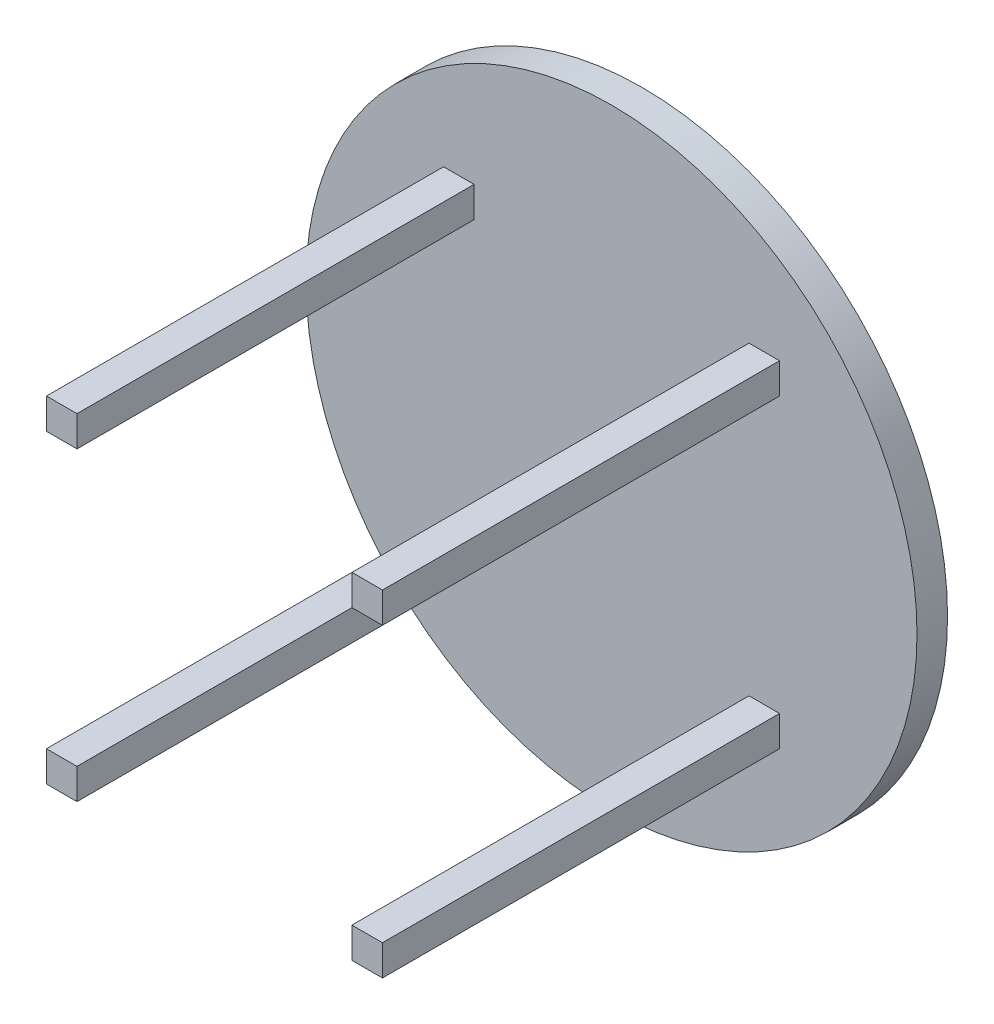
SolidWorks part; units mm, degrees
ref_plane "前视基准面" through (0, 0, 0) normal (0, 0, 1) x (1, 0, 0)
ref_plane "上视基准面" through (0, 0, 0) normal (0, 1, 0) x (1, 0, 0)
ref_plane "右视基准面" through (0, 0, 0) normal (1, 0, 0) x (0, 0, -1)
other "Configuration Table"
sketch "草图1" plane through (0, 0, 0) normal (0, 0, 1) x (1, 0, 0)
  circle A0 centre (0, 0) radius 500
extrude "凸台-拉伸1" add sketch "草图1" along normal blind 50
sketch "草图2" plane through (0, 0, 0) normal (0, 0, 1) x (1, 0, 0)
  line L1 (225, 225) -> (275, 225)
  line L2 (225, 225) -> (225, 275)
  line L3 (225, 275) -> (275, 275)
  line L4 (275, 225) -> (275, 275)
  line L5 (225, 225) -> (275, 275) construction
  line L6 (225, 275) -> (275, 225) construction
  point P0 (250, 250)
extrude "凸台-拉伸2" add sketch "草图2" along normal blind 700
sketch "草图3" plane through (0, 0, 0) normal (0, 0, 1) x (1, 0, 0)
  line L1 (-275, 225) -> (-225, 225)
  line L2 (-275, 225) -> (-275, 275)
  line L3 (-275, 275) -> (-225, 275)
  line L4 (-225, 225) -> (-225, 275)
  line L5 (-275, 225) -> (-225, 275) construction
  line L6 (-275, 275) -> (-225, 225) construction
  point P0 (-250, 250)
extrude "凸台-拉伸3" add sketch "草图3" along normal blind 700
sketch "草图4" plane through (0, 0, 0) normal (0, 0, 1) x (1, 0, 0)
  line L1 (225, -275) -> (275, -275)
  line L2 (225, -275) -> (225, -225)
  line L3 (225, -225) -> (275, -225)
  line L4 (275, -275) -> (275, -225)
  line L5 (225, -275) -> (275, -225) construction
  line L6 (225, -225) -> (275, -275) construction
  point P0 (250, -250)
extrude "凸台-拉伸4" add sketch "草图4" along normal blind 700
sketch "草图5" plane through (0, 0, 0) normal (0, 0, 1) x (1, 0, 0)
  line L1 (-275, -275) -> (-225, -275)
  line L2 (-275, -275) -> (-275, -225)
  line L3 (-275, -225) -> (-225, -225)
  line L4 (-225, -275) -> (-225, -225)
  line L5 (-275, -275) -> (-225, -225) construction
  line L6 (-275, -225) -> (-225, -275) construction
  point P0 (-250, -250)
extrude "凸台-拉伸5" add sketch "草图5" along normal blind 700
sketch "草图6" plane through (0, 275, 0) normal (0, 1, 0) x (1, 0, 0)
  line L1 (-100, -50) -> (100, -50)
  line L2 (-100, -50) -> (-100, 50)
  line L3 (-100, 50) -> (100, 50)
  line L4 (100, -50) -> (100, 50)
  line L5 (-100, -50) -> (100, 50) construction
  line L6 (-100, 50) -> (100, -50) construction
  point P0 (0, 0)
extrude "凸台-拉伸6" add sketch "草图6" along normal blind 50
sketch "草图7" plane through (0, 275, 0) normal (0, 1, 0) x (1, 0, 0)
  line L1 (-75, -25) -> (75, -25)
  line L2 (-75, -25) -> (-75, 25)
  line L3 (-75, 25) -> (75, 25)
  line L4 (75, -25) -> (75, 25)
  line L5 (-75, -25) -> (75, 25) construction
  line L6 (-75, 25) -> (75, -25) construction
  point P0 (0, 0)
extrude "切除-拉伸1" cut sketch "草图7" against normal blind 30
